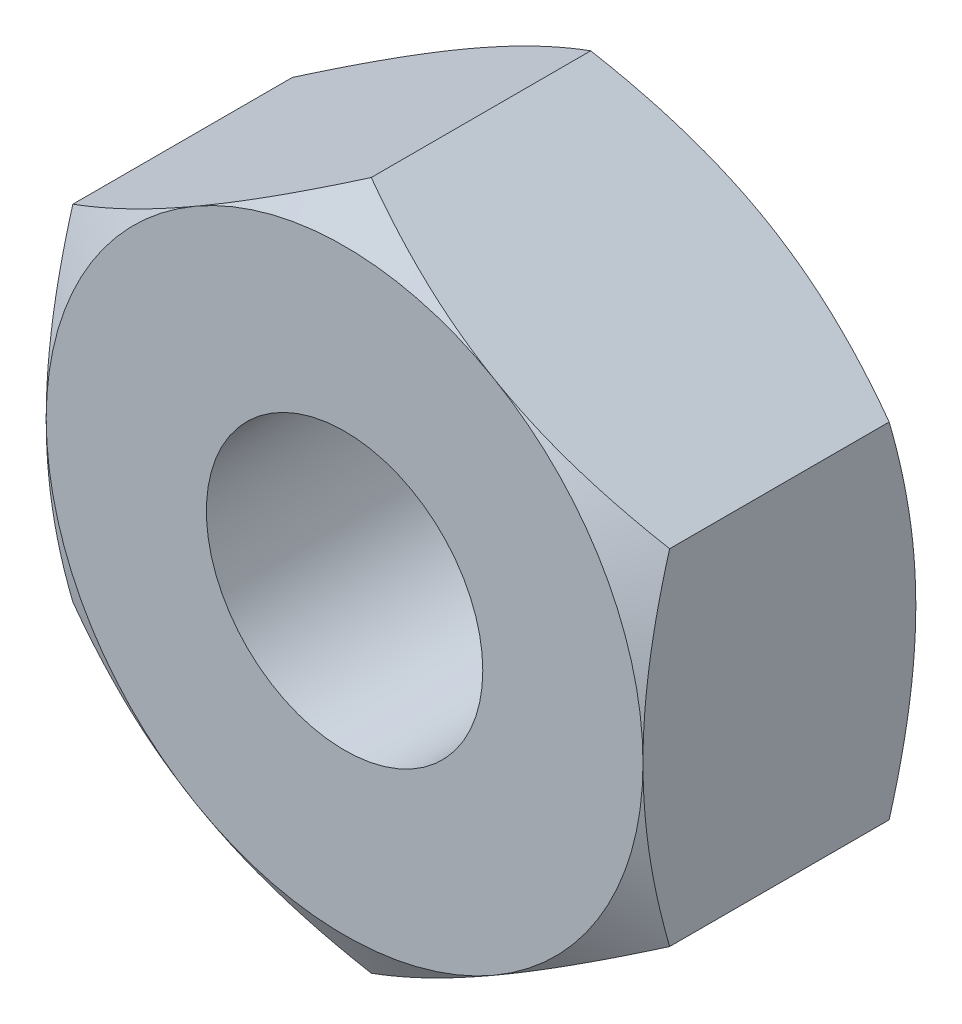
SolidWorks part; units mm, degrees
ref_plane "基准面1" through (0, 0, 0) normal (0, 0, 1) x (1, 0, 0)
ref_plane "基准面2" through (0, 0, 0) normal (0, 1, 0) x (1, 0, 0)
ref_plane "基准面3" through (0, 0, 0) normal (1, 0, 0) x (0, 0, -1)
sketch "草图1" plane through (0, 0, 0) normal (0, 0, 1) x (1, 0, 0)
  line L0 (-3.5, 0) -> (3.5, 0) construction
  line L1 (0, 4.0415) -> (0, -4.0415) construction
  line L3 (0, 4.0415) -> (-3.5, 2.0207)
  line L4 (-3.5, 2.0207) -> (-3.5, -2.0207)
  line L5 (-3.5, -2.0207) -> (0, -4.0415)
  line L6 (0, -4.0415) -> (3.5, -2.0207)
  line L7 (3.5, -2.0207) -> (3.5, 2.0207)
  line L8 (3.5, 2.0207) -> (0, 4.0415)
  circle A0 centre (0, 0) radius 3.5 construction
  circle A1 centre (0, 0) radius 1.6211
  point P2 (0, 3.6585)
  dimension "D1" = 7.7
  dimension "D" = 3.2422
  dimension "D2" = 7
extrude "基体-拉伸" add sketch "草图1" along normal blind 3.2
cosmetic thread "装饰螺纹线1" parameters "D2"=4
sketch "草图2" plane through (0, 0, 0) normal (0, 0, -1) x (-1, 0, 0)
  circle A0 centre (0, 0) radius 3.5
  circle A1 centre (0, 0) radius 1.6211 construction
  dimension "s" = 7
extrude "切除-拉伸1" cut sketch "草图2" against normal through all draft 60 flip side to cut
sketch "草图3" plane through (0, 0, 3.2) normal (0, 0, 1) x (1, 0, 0)
  circle A0 centre (0, 0) radius 3.5
  dimension "D1" = 7
extrude "切除-拉伸2" cut sketch "草图3" against normal through all draft 60 flip side to cut
